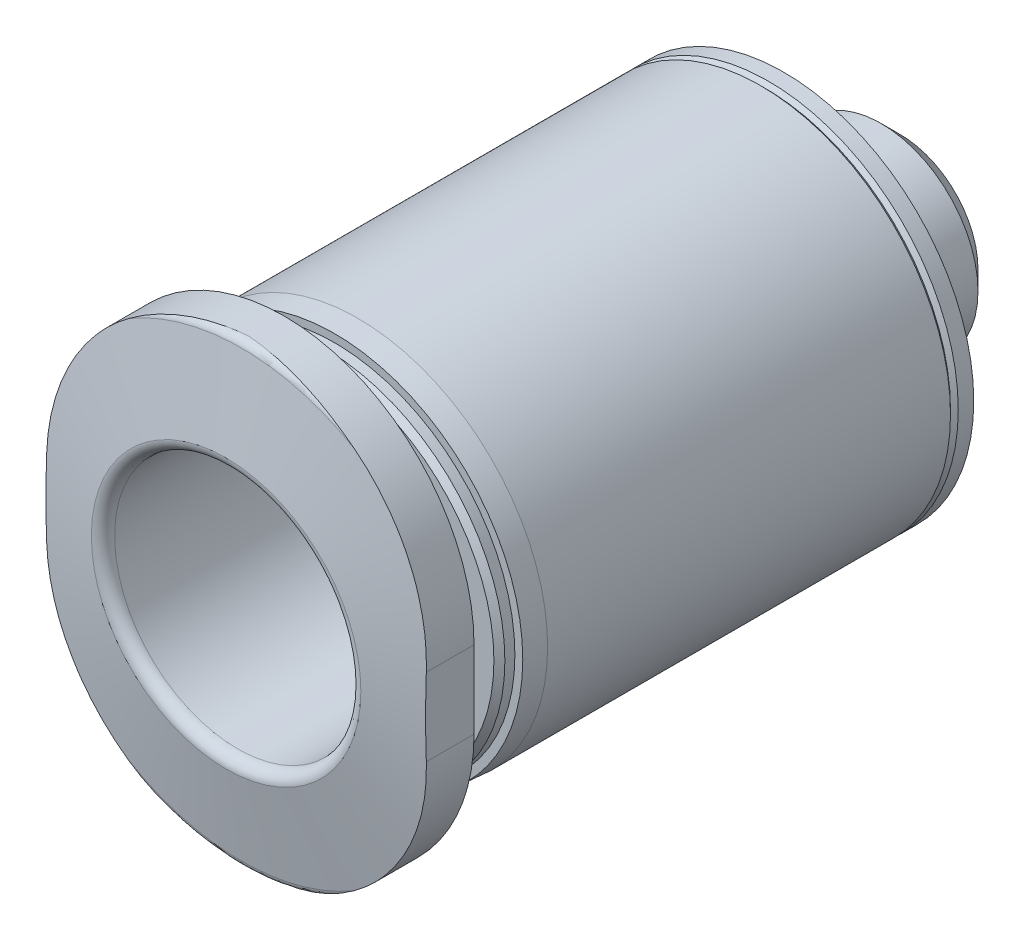
SolidWorks part; units mm, degrees
ref_plane "Front Plane" through (0, 0, 0) normal (0, 0, 1) x (1, 0, 0)
ref_plane "Top Plane" through (0, 0, 0) normal (0, 1, 0) x (1, 0, 0)
ref_plane "Right Plane" through (0, 0, 0) normal (1, 0, 0) x (0, 0, -1)
ref_plane "Plane1" through (0, 0, 0) normal (1, 0, 0) x (0, 0, -1)
sketch "Sketch1" plane through (0, 0, 0) normal (1, 0, 0) x (0, 0, -1)
  line L0 (-14.4, 0) -> (-14.4, 3.4785)
  line L1 (-14.4, 3.4785) -> (-14.0022, 5.7347)
  line L2 (-13.8052, 5.9) -> (-12.9, 5.9)
  line L3 (-12.9, 5.9) -> (-12.9, 4.2535)
  line L4 (-12.525, 3.8785) -> (-12, 3.8785)
  line L5 (-12, 3.8785) -> (-12, 4.5136)
  line L6 (-12, 4.5136) -> (-11.8586, 4.655)
  line L7 (-11.8586, 4.655) -> (-11.6, 4.655)
  line L8 (-11.6, 4.655) -> (-11.6, 4.858)
  line L9 (-11.6, 4.858) -> (-11, 4.9)
  line L10 (-11, 4.9) -> (-0.6, 4.9)
  line L11 (-0.6, 4.9) -> (-0.5, 4.8)
  line L12 (-0.5, 4.8) -> (-0.4, 4.9)
  line L13 (-0.4, 4.9) -> (0, 4.9)
  line L14 (0, 4.9) -> (0, 2.5)
  line L15 (0, 2.5) -> (2.5095, 2.5)
  line L16 (2.5095, 2.5) -> (3, 2.0095)
  line L17 (3, 2.0095) -> (3, 0)
  line L18 (3, 0) -> (-14.4, 0)
  line L19 (3, 0) -> (-14.4, 0) construction
  arc A0 (-14.0022, 5.7347) -> (-13.8052, 5.9) centre (-13.8052, 5.7) cw
  arc A1 (-12.9, 4.2535) -> (-12.525, 3.8785) centre (-12.525, 4.2535) ccw
revolve "Revolve1" add sketch "Sketch1" angle 360 about L19
cosmetic thread "Cosmetic Thread1" parameters "D1"=2.5, "D2"=4.019
ref_plane "Plane2" through (0, 0, 14.4) normal (0, 0, 1) x (1, 0, 0)
sketch "Sketch2" plane through (0, 0, 14.4) normal (0, 0, 1) x (1, 0, 0)
  line L0 (-11.8, -11.8) -> (11.8, -11.8)
  line L1 (11.8, -11.8) -> (11.8, 11.8)
  line L2 (11.8, 11.8) -> (-11.8, 11.8)
  line L3 (-11.8, 11.8) -> (-11.8, -11.8)
  line L4 (-4.9, 1) -> (-4.9, -1)
  line L5 (4.9, -1) -> (4.9, 1)
  arc A0 (-4.9, -1) -> (4.9, -1) centre (0, -1) ccw
  arc A1 (4.9, 1) -> (-4.9, 1) centre (0, 1) ccw
extrude "Cut-Extrude1" cut sketch "Sketch2" against normal blind 1.5
ref_plane "Plane3" through (0, 0, -3) normal (0, 0, 1) x (1, 0, 0)
sketch "Sketch3" plane through (0, 0, -3) normal (0, 0, 1) x (1, 0, 0)
  line L0 (-1.25, -0.7217) -> (0, -1.4434)
  line L1 (0, -1.4434) -> (1.25, -0.7217)
  line L2 (1.25, -0.7217) -> (1.25, 0.7217)
  line L3 (1.25, 0.7217) -> (0, 1.4434)
  line L4 (0, 1.4434) -> (-1.25, 0.7217)
  line L5 (-1.25, 0.7217) -> (-1.25, -0.7217)
extrude "Cut-Extrude2" cut sketch "Sketch3" along normal blind 5.7
ref_plane "Plane4" through (0, 0, 0) normal (1, 0, 0) x (0, 0, -1)
sketch "Sketch4" plane through (0, 0, 0) normal (1, 0, 0) x (0, 0, -1)
  line L0 (-14.4, 0) -> (-14.4, 3.4785)
  line L1 (-14.1, 3.1785) -> (-2.7, 3.1785)
  line L2 (-2.7, 3.1785) -> (-2.7, 0)
  line L3 (-2.7, 0) -> (-14.4, 0)
  line L4 (-2.7, 0) -> (-14.4, 0) construction
  arc A0 (-14.4, 3.4785) -> (-14.1, 3.1785) centre (-14.1, 3.4785) ccw
revolve "Cut-Revolve1" cut sketch "Sketch4" angle 360 about L4
